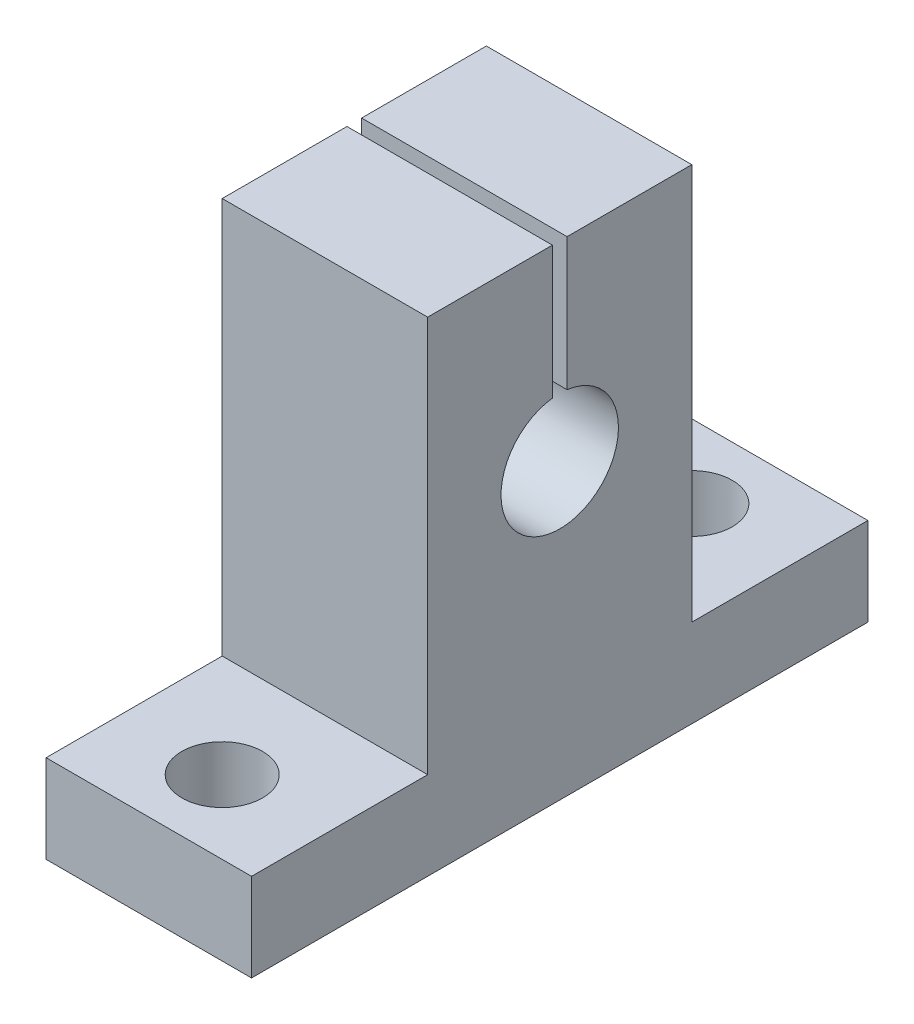
SolidWorks part; units mm, degrees
ref_plane "Front Plane" through (0, 0, 0) normal (0, 0, 1) x (1, 0, 0)
ref_plane "Top Plane" through (0, 0, 0) normal (0, 1, 0) x (1, 0, 0)
ref_plane "Right Plane" through (0, 0, 0) normal (1, 0, 0) x (0, 0, -1)
sketch "Sketch1" plane through (0, 0, 0) normal (1, 0, 0) x (0, 0, -1)
  line L0 (21, -20) -> (-21, -20)
  line L1 (-21, -20) -> (-21, -14)
  line L2 (-21, -14) -> (-9, -14)
  line L3 (-9, -14) -> (-9, 13)
  line L4 (-9, 13) -> (-0.5, 13)
  line L5 (0, -20) -> (0, 13) construction
  line L6 (-0.5, 13) -> (-0.5, 3.9686)
  line L7 (0.5, 13) -> (0.5, 3.9686)
  line L8 (9, 13) -> (0.5, 13)
  line L9 (9, -14) -> (9, 13)
  line L10 (21, -14) -> (9, -14)
  line L11 (21, -20) -> (21, -14)
  arc A0 (-0.5, 3.9686) -> (0.5, 3.9686) centre (0, 0) ccw
  dimension "D1" = 8
  dimension "D2" = 21
  dimension "D3" = 6
  dimension "D4" = 33
  dimension "D5" = 9
  dimension "D6" = 13
  dimension "D7" = 0.5
extrude "Boss-Extrude1" add sketch "Sketch1" along normal blind 14
sketch "Sketch2" plane through (0, -14, 0) normal (0, 1, 0) x (1, 0, 0)
  line L0 (7, 21) -> (7, -21) construction
  line L1 (14, 21) -> (0, 21) construction
  line L2 (14, -21) -> (0, -21) construction
  line L3 (0, 0) -> (14, 0) construction
  line L4 (14, -4) -> (14, 4) construction
  circle A0 centre (7, 16) radius 2.75
  circle A1 centre (7, -16) radius 2.75
  dimension "D1" = 5.5
  dimension "D2" = 16
extrude "Cut-Extrude1" cut sketch "Sketch2" against normal through all both and the other way through all
